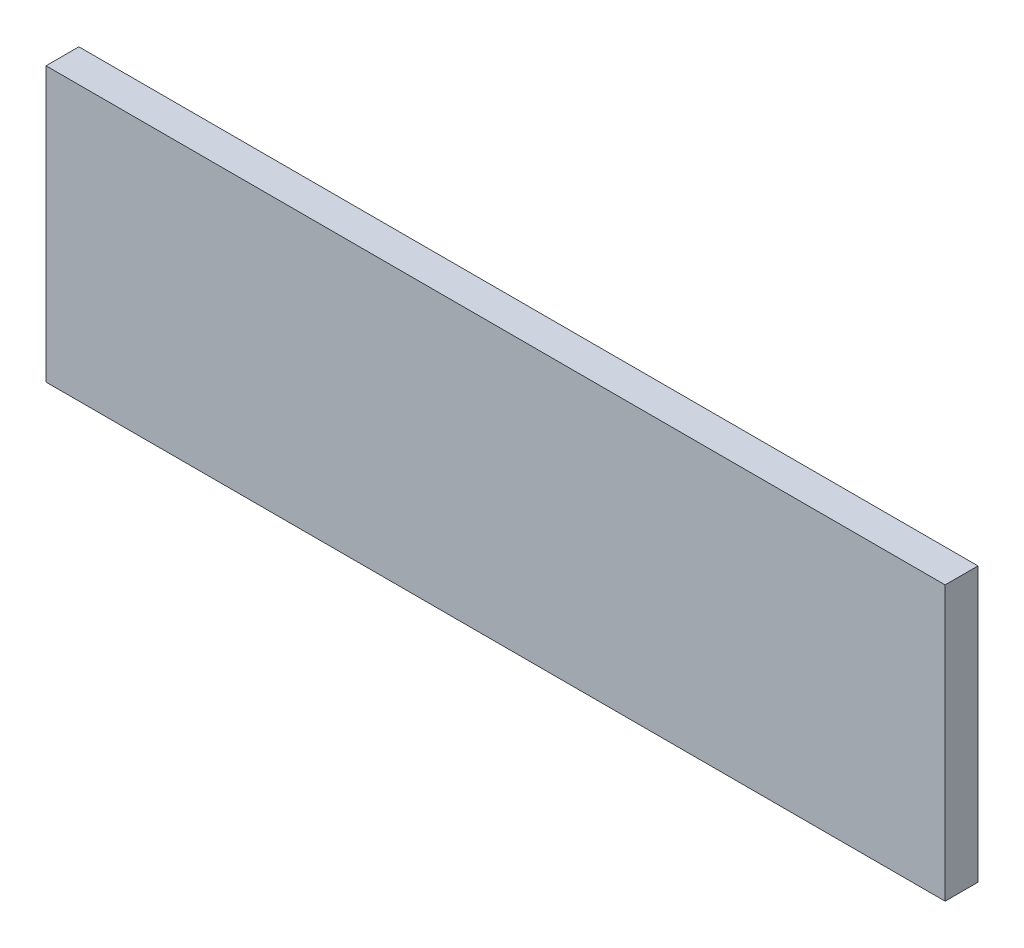
SolidWorks part; units mm, degrees
ref_plane "Спереди" through (0, 0, 0) normal (0, 0, 1) x (1, 0, 0)
ref_plane "Сверху" through (0, 0, 0) normal (0, 1, 0) x (1, 0, 0)
ref_plane "Справа" through (0, 0, 0) normal (1, 0, 0) x (0, 0, -1)
other "Configuration Table"
sketch "Эскиз1" plane through (0, 0, 0) normal (0, 0, 1) x (1, 0, 0)
  line L1 (82.05, 25) -> (-82.05, 25)
  line L2 (82.05, 25) -> (82.05, -25)
  line L3 (82.05, -25) -> (-82.05, -25)
  line L4 (-82.05, 25) -> (-82.05, -25)
  line L5 (82.05, 25) -> (-82.05, -25) construction
  line L6 (82.05, -25) -> (-82.05, 25) construction
  point P0 (0, 0)
  dimension "D1" = 50
  dimension "D2" = 164.1
extrude "Бобышка-Вытянуть1" add sketch "Эскиз1" along normal blind 6
